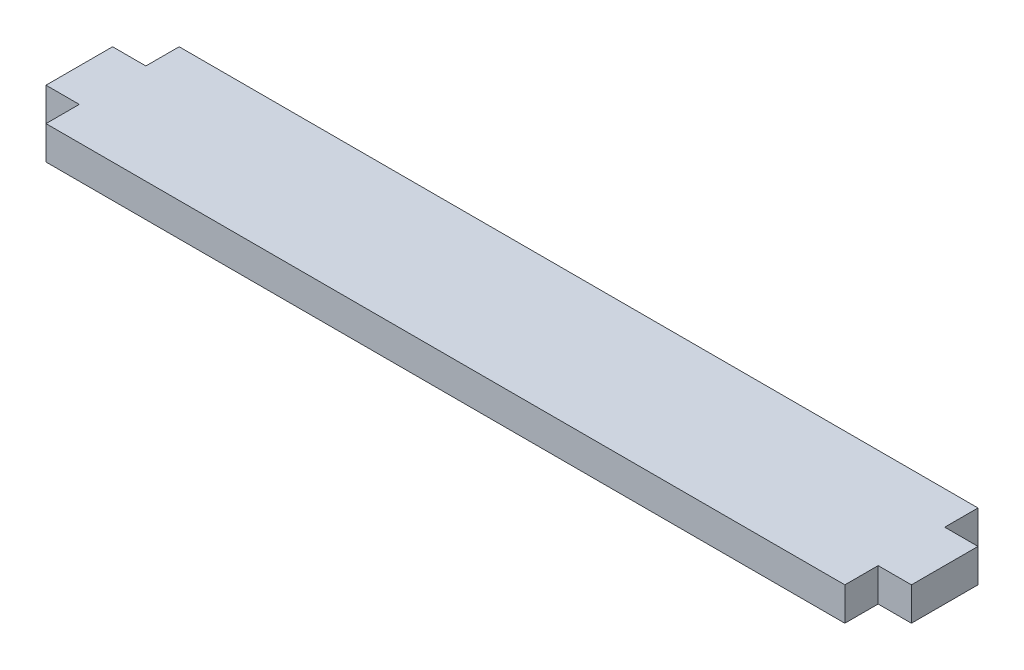
SolidWorks part; units mm, degrees
ref_plane "Front Plane" through (0, 0, 0) normal (0, 0, 1) x (1, 0, 0)
ref_plane "Top Plane" through (0, 0, 0) normal (0, 1, 0) x (1, 0, 0)
ref_plane "Right Plane" through (0, 0, 0) normal (1, 0, 0) x (0, 0, -1)
sketch "Sketch1" plane through (0, 0, 0) normal (0, 1, 0) x (1, 0, 0)
  line L1 (0, 0) -> (152.4, 0)
  line L2 (0, 0) -> (0, -25.4)
  line L3 (0, -25.4) -> (152.4, -25.4)
  line L4 (152.4, 0) -> (152.4, -25.4)
  dimension "D1" = 25.4
  dimension "D2" = 152.4
extrude "Boss-Extrude1" add sketch "Sketch1" along normal blind 6.35
sketch "Sketch3" plane through (0, 6.35, 0) normal (0, 1, 0) x (1, 0, 0)
  line L0 (0, 0) -> (0, -25.4) construction
  line L1 (0, -6.35) -> (-6.35, -6.35)
  line L2 (0, -6.35) -> (0, -19.05)
  line L3 (0, -19.05) -> (-6.35, -19.05)
  line L4 (-6.35, -6.35) -> (-6.35, -19.05)
  line L5 (152.4, -12.7) -> (-6.35, -12.7) construction
  line L6 (152.4, -25.4) -> (152.4, 0) construction
  line L7 (0, -25.4) -> (152.4, -25.4) construction
  point P10 (-6.35, -12.7)
  point P13 (-6.35, -12.7)
  dimension "D1" = 12.7
  dimension "D2" = 6.35
extrude "Boss-Extrude2" add sketch "Sketch3" against normal blind 6.35
ref_plane "Plane1" through (76.2, 0, 0) normal (-1, 0, 0) x (0, 0, 1)
mirror "Mirror1" about plane through (76.2, 0, 0) normal (-1, 0, 0) of "Boss-Extrude2"
